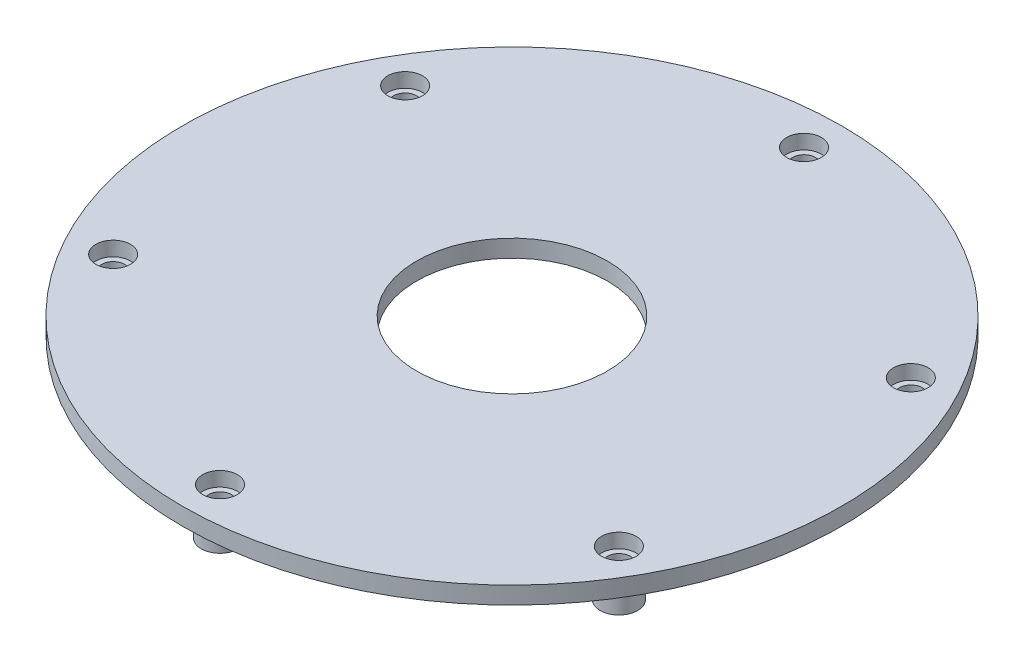
SolidWorks part; units mm, degrees
ref_plane "Front Plane" through (0, 0, 0) normal (0, 0, 1) x (1, 0, 0)
ref_plane "Top Plane" through (0, 0, 0) normal (0, 1, 0) x (1, 0, 0)
ref_plane "Right Plane" through (0, 0, 0) normal (1, 0, 0) x (0, 0, -1)
sketch "Sketch1" plane through (0, 0, 0) normal (0, 1, 0) x (1, 0, 0)
  circle A0 centre (0, 0) radius 57
  dimension "D1" = 114
extrude "Boss-Extrude1" add sketch "Sketch1" along normal blind 3
sketch "Sketch2" plane through (0, 3, 0) normal (0, 1, 0) x (1, 0, 0)
  line L0 (0, 62.5097) -> (0, -64.2706) construction
  circle A0 centre (0, 50.5) radius 2
  dimension "D1" = 4
  dimension "D2" = 50.5
extrude "Cut-Extrude1" cut sketch "Sketch2" against normal through all
pattern_circular "CirPattern1" count 6 over 360 about axis through (0, 0, 0) along (0, 1, 0) of "Cut-Extrude1"
sketch "Sketch5" plane through (0, 0, 0) normal (0, -1, 0) x (1, 0, 0)
  circle A0 centre (0, 50.5) radius 3.25
  circle A1 centre (43.7343, 25.25) radius 3.25
  circle A2 centre (43.7343, -25.25) radius 3.25
  circle A3 centre (0, -50.5) radius 3.25
  circle A4 centre (-43.7343, -25.25) radius 3.25
  circle A5 centre (-43.7343, 25.25) radius 3.25
  dimension "D1" = 6.5
  dimension "D2" = 6.5
extrude "Boss-Extrude2" add sketch "Sketch5" along normal blind 5
sketch "Sketch4" plane through (0, 0, 0) normal (0, -1, 0) x (1, 0, 0)
  circle A0 centre (0, 0) radius 16.5
  dimension "D1" = 33
extrude "Cut-Extrude3" cut sketch "Sketch4" against normal through all
sketch "Sketch8" plane through (0, 3, 0) normal (0, 1, 0) x (1, 0, 0)
  circle A0 centre (-43.7343, -25.25) radius 2 construction
  circle A1 centre (0, -50.5) radius 2 construction
  circle A2 centre (43.7343, -25.25) radius 2 construction
  circle A3 centre (43.7343, 25.25) radius 2 construction
  circle A4 centre (0, 50.5) radius 2 construction
  circle A5 centre (-43.7343, 25.25) radius 2 construction
  circle A6 centre (-43.7343, -25.25) radius 2
  circle A7 centre (0, -50.5) radius 2
  circle A8 centre (43.7343, -25.25) radius 2
  circle A9 centre (43.7343, 25.25) radius 2
  circle A10 centre (0, 50.5) radius 2
  circle A11 centre (-43.7343, 25.25) radius 2
extrude "Cut-Extrude4" cut sketch "Sketch8" against normal through all
sketch "Sketch9" plane through (0, 3, 0) normal (0, 1, 0) x (1, 0, 0)
  circle A0 centre (-43.7343, 25.25) radius 3
  circle A1 centre (0, 50.5) radius 3
  circle A2 centre (43.7343, 25.25) radius 3
  circle A3 centre (43.7343, -25.25) radius 3
  circle A4 centre (0, -50.5) radius 3
  circle A5 centre (-43.7343, -25.25) radius 3
  dimension "D1" = 6
extrude "Cut-Extrude5" cut sketch "Sketch9" against normal blind 2.5
